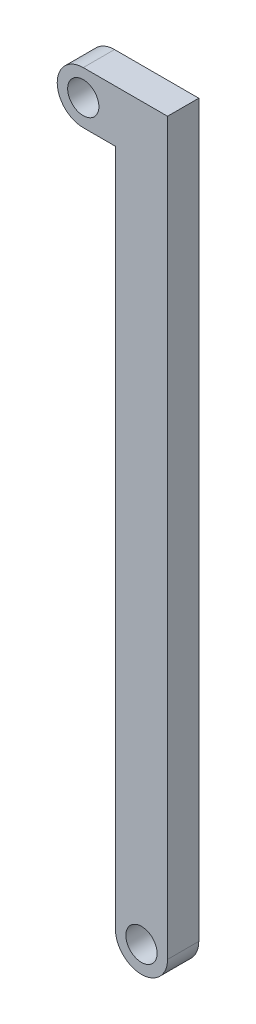
SolidWorks part; units mm, degrees
ref_plane "Front Plane" through (0, 0, 0) normal (0, 0, 1) x (1, 0, 0)
ref_plane "Top Plane" through (0, 0, 0) normal (0, 1, 0) x (1, 0, 0)
ref_plane "Right Plane" through (0, 0, 0) normal (1, 0, 0) x (0, 0, -1)
sketch "Sketch1" plane through (0, 0, 0) normal (0, 0, 1) x (1, 0, 0)
  line L0 (-119.5639, 71.4278) -> (-63.6639, 71.4278) construction
  line L1 (-63.6639, 71.4278) -> (-63.6639, -604.5722) construction
  line L2 (-119.5639, 46.4278) -> (-88.6639, 46.4278)
  line L3 (-88.6639, 46.4278) -> (-88.6639, -604.5722)
  line L4 (-119.5639, 96.4278) -> (-38.6639, 96.4278)
  line L5 (-38.6639, 96.4278) -> (-38.6639, -604.5722)
  circle A0 centre (-119.5639, 71.4278) radius 15
  circle A1 centre (-63.6639, -604.5722) radius 15
  arc A2 (-119.5639, 46.4278) -> (-119.5639, 96.4278) centre (-119.5639, 71.4278) cw
  arc A3 (-88.6639, -604.5722) -> (-38.6639, -604.5722) centre (-63.6639, -604.5722) ccw
  dimension "D3" = 25
  dimension "D1" = 55.9
  dimension "D2" = 676
  dimension "D4" = 25
extrude "Boss-Extrude1" add sketch "Sketch1" along normal blind 30
